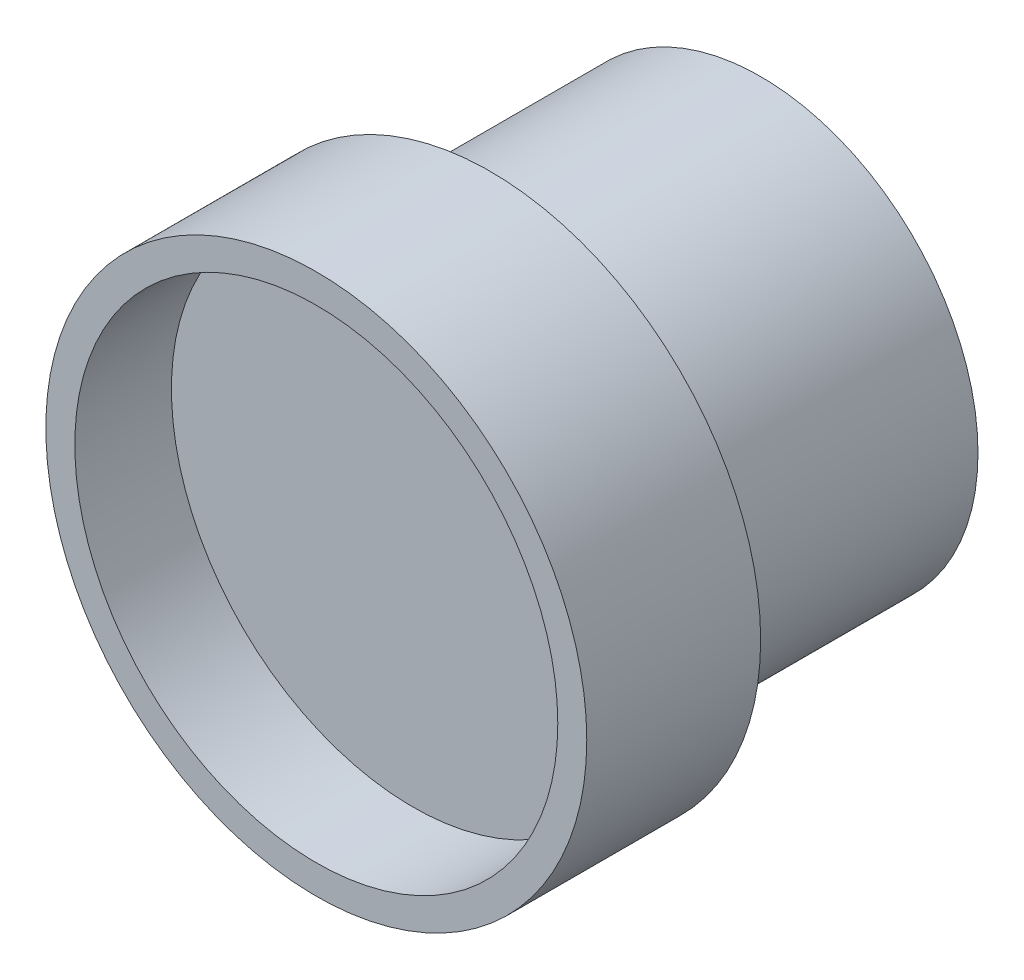
SolidWorks part; units mm, degrees
material "PW80:Mi:0:41:Ar:0:-1:C1:1:2:3:Re:15:"
ref_plane "Plan1" through (0, 0, 0) normal (0, 0, 1) x (1, 0, 0)
ref_plane "Plan2" through (0, 0, 0) normal (0, 1, 0) x (1, 0, 0)
ref_plane "Plan3" through (0, 0, 0) normal (1, 0, 0) x (0, 0, -1)
sketch "Esquisse1" plane through (0, 0, 0) normal (0, 0, 1) x (1, 0, 0)
  circle A0 centre (0, 0) radius 11.25
extrude "Base-Extrusion" add sketch "Esquisse1" along normal blind 14
sketch "Esquisse2" plane through (0, 0, 14) normal (0, 0, 1) x (1, 0, 0)
  circle A0 centre (0, 0) radius 14
extrude "Boss.-Extru.1" add sketch "Esquisse2" along normal blind 9
sketch "Esquisse3" plane through (0, 0, 23) normal (0, 0, 1) x (1, 0, 0)
  circle A0 centre (0, 0) radius 12.5
extrude "Enlèv. mat.-Extru.1" cut sketch "Esquisse3" against normal blind 5
